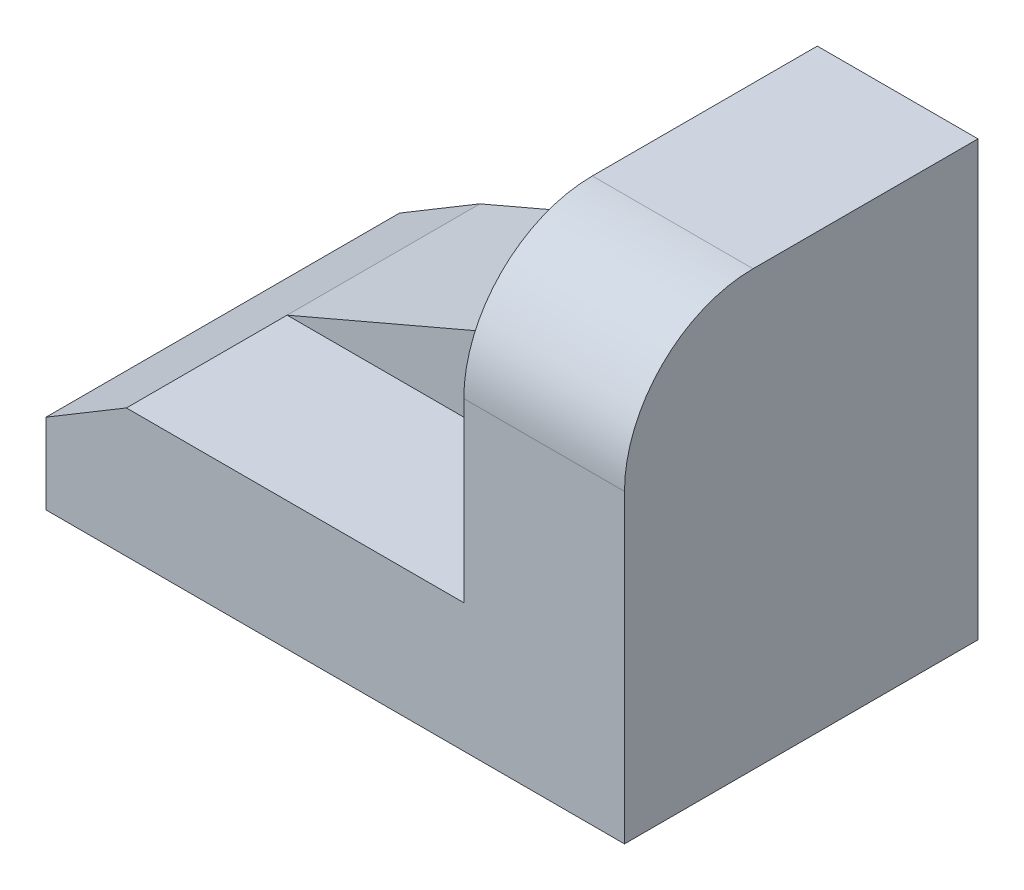
SolidWorks part; units mm, degrees
ref_plane "Front Plane" through (0, 0, 0) normal (0, 0, 1) x (1, 0, 0)
ref_plane "Top Plane" through (0, 0, 0) normal (0, 1, 0) x (1, 0, 0)
ref_plane "Right Plane" through (0, 0, 0) normal (1, 0, 0) x (0, 0, -1)
sketch "Sketch2" plane through (0, 0, 0) normal (0, 0, 1) x (1, 0, 0)
  line L0 (0, 0) -> (36000, 0)
  line L1 (36000, 0) -> (36000, 27000)
  line L2 (36000, 27000) -> (26000, 27000)
  line L3 (26000, 27000) -> (26000, 8000)
  line L4 (0, 0) -> (0, 5000)
  line L5 (0, 5000) -> (5004.2282, 8000)
  line L6 (5004.2282, 8000) -> (26000, 8000)
  dimension "D1" = 36000
  dimension "D2" = 27000
  dimension "D3" = 10000
  dimension "D4" = 3000
  dimension "D5" = 5000
extrude "Boss-Extrude1" add sketch "Sketch2" along normal blind 22000
sketch "Sketch3" plane through (36000, 0, 0) normal (1, 0, 0) x (0, 0, -1)
  line L0 (-22000, 19000) -> (-22000, 27000)
  line L1 (-22000, 27000) -> (-14000, 27000)
  arc A0 (-22000, 19000) -> (-14000, 27000) centre (-14000, 19000) cw
  point P8 (-22000, 27000)
  dimension "D1" = 8000
extrude "Cut-Extrude1" cut sketch "Sketch3" against normal blind 22000
sketch "Sketch4" plane through (0, 0, 0) normal (0, 0, -1) x (-1, 0, 0)
  line L0 (-5004.2282, 8000) -> (-26000, 8000)
  line L1 (-26000, 8000) -> (-26000, 17000)
  line L2 (-26000, 27000) -> (-26000, 8000) construction
  line L3 (-26000, 17000) -> (-5004.2282, 8000)
  dimension "D1" = 12000
extrude "Boss-Extrude2" add sketch "Sketch4" against normal blind 12000
